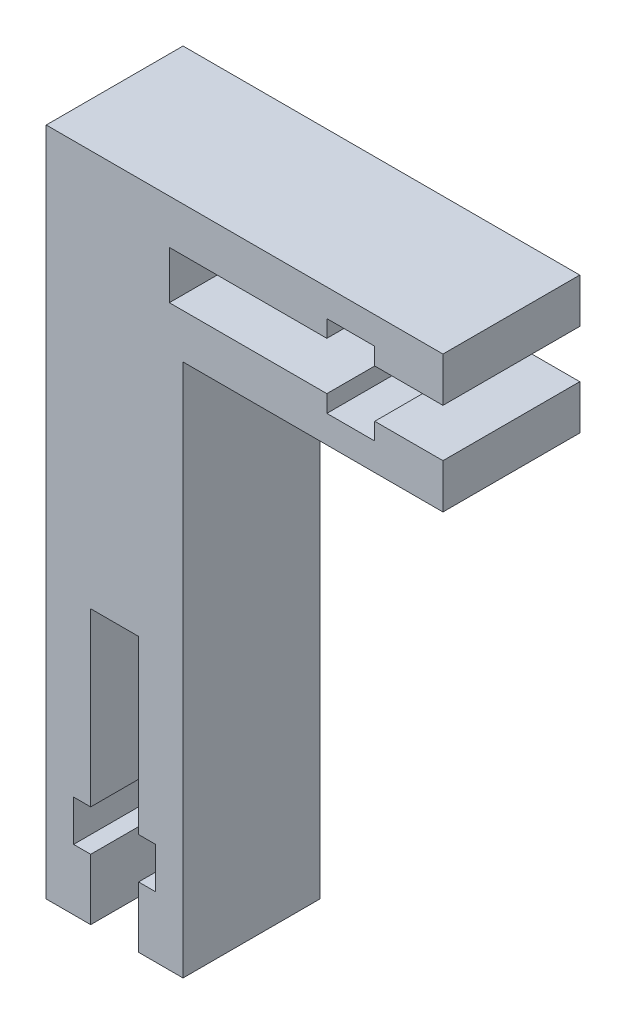
SolidWorks part; units mm, degrees
ref_plane "Front Plane" through (0, 0, 0) normal (0, 0, 1) x (1, 0, 0)
ref_plane "Top Plane" through (0, 0, 0) normal (0, 1, 0) x (1, 0, 0)
ref_plane "Right Plane" through (0, 0, 0) normal (1, 0, 0) x (0, 0, -1)
sketch "Esquisse1" plane through (0, 0, 0) normal (0, 0, 1) x (1, 0, 0)
  line L0 (0, 0) -> (3.25, 0)
  line L1 (10, 0) -> (10, 39)
  line L2 (10, 39) -> (29, 39)
  line L3 (29, 39) -> (29, 42.25)
  line L4 (29, 49) -> (0, 49)
  line L5 (0, 49) -> (0, 0)
  line L6 (3.25, 0) -> (3.25, 4.4564)
  line L7 (3.25, 4.4564) -> (2, 4.4564)
  line L8 (2, 4.4564) -> (2, 7.4564)
  line L9 (2, 7.4564) -> (3.25, 7.4564)
  line L10 (8, 7.4564) -> (8, 4.4564)
  line L11 (8, 4.4564) -> (6.75, 4.4564)
  line L12 (6.75, 4.4564) -> (6.75, 0)
  line L13 (3.25, 7.4564) -> (3.25, 20)
  line L14 (3.25, 20) -> (6.75, 20)
  line L15 (6.75, 20) -> (6.75, 7.4564)
  line L16 (6.75, 7.4564) -> (8, 7.4564)
  line L17 (6.75, 0) -> (10, 0)
  line L18 (29, 45.75) -> (24.013, 45.75)
  line L19 (24.013, 45.75) -> (24.013, 47)
  line L20 (24.013, 47) -> (20.513, 47)
  line L21 (20.513, 47) -> (20.513, 45.75)
  line L22 (20.513, 45.75) -> (9, 45.75)
  line L23 (9, 45.75) -> (9, 42.25)
  line L24 (9, 42.25) -> (20.513, 42.25)
  line L25 (20.513, 42.25) -> (20.513, 41)
  line L26 (20.513, 41) -> (24.013, 41)
  line L27 (24.013, 41) -> (24.013, 42.25)
  line L28 (24.013, 42.25) -> (29, 42.25)
  line L29 (29, 45.75) -> (29, 49)
  dimension "D1" = 10
  dimension "D2" = 39
  dimension "D3" = 10
  dimension "D4" = 19
  dimension "D5" = 6
  dimension "D6" = 3
  dimension "D7" = 20
  dimension "D8" = 6
  dimension "D9" = 20
  dimension "D10" = 3.5
  dimension "D11" = 3.5
  dimension "D12" = 3.5
  dimension "D13" = 3.5
extrude "Boss.-Extru.1" add sketch "Esquisse1" along normal blind 10
